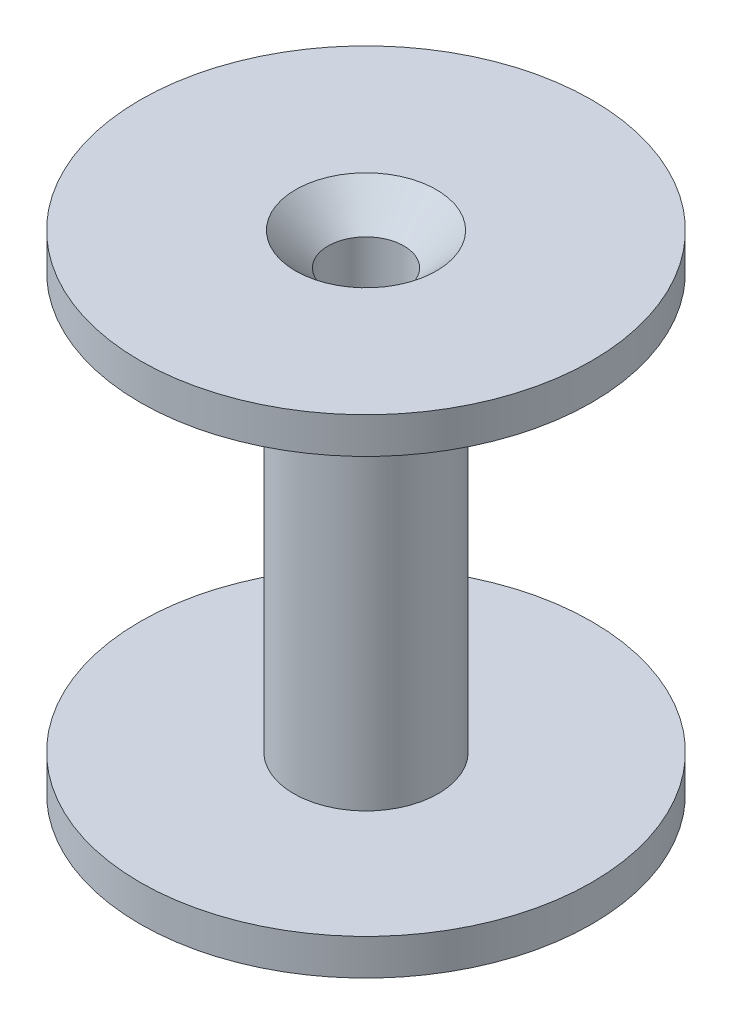
SolidWorks part; units mm, degrees
material "ABS"
ref_plane "Front Plane" through (0, 0, 0) normal (0, 0, 1) x (1, 0, 0)
ref_plane "Top Plane" through (0, 0, 0) normal (0, 1, 0) x (1, 0, 0)
ref_plane "Right Plane" through (0, 0, 0) normal (1, 0, 0) x (0, 0, -1)
sketch "Sketch1" plane through (0, 0, 0) normal (1, 0, 0) x (0, 0, -1)
  line L0 (0, 40.3784) -> (0, -34.9054) construction
  line L1 (-4, 11.5) -> (-4, -11.5)
  line L2 (-4, -11.5) -> (-12.5, -11.5)
  line L3 (-12.5, -11.5) -> (-12.5, -13.5)
  line L4 (-12.5, -13.5) -> (-2.1, -13.5)
  line L5 (0, 0) -> (-27, 0) construction
  line L6 (-12.5, 13.5) -> (-3.8981, 13.5)
  line L7 (-12.5, 11.5) -> (-12.5, 13.5)
  line L8 (-4, 11.5) -> (-12.5, 11.5)
  line L9 (-2.1, 11.7019) -> (-2.1, -13.5)
  line L10 (-3.8981, 13.5) -> (-2.1, 11.7019)
  point P10 (-4, 0)
  dimension "D1" = 8
  dimension "D2" = 4.2
  dimension "D3" = 25
  dimension "D4" = 27
  dimension "D5" = 2
  dimension "D6" = 135
revolve "Revolve1" add sketch "Sketch1" angle 360 about L0
